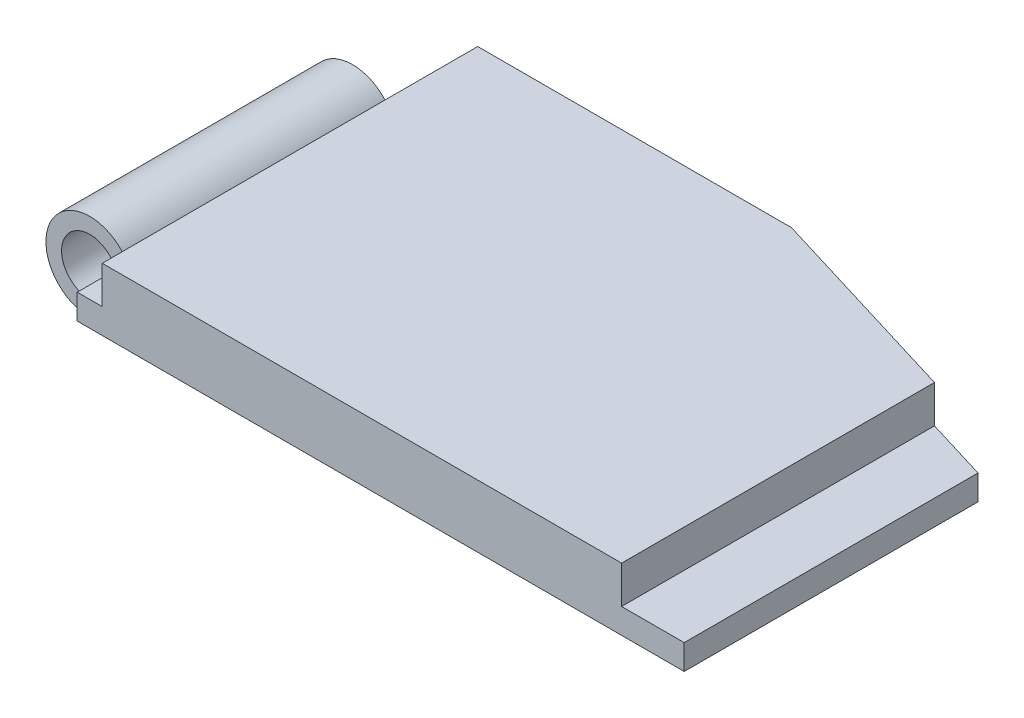
SolidWorks part; units mm, degrees
ref_plane "Front Plane" through (0, 0, 0) normal (0, 0, 1) x (1, 0, 0)
ref_plane "Top Plane" through (0, 0, 0) normal (0, 1, 0) x (1, 0, 0)
ref_plane "Right Plane" through (0, 0, 0) normal (1, 0, 0) x (0, 0, -1)
sketch "Sketch1" plane through (0, 0, 0) normal (0, 1, 0) x (1, 0, 0)
  line L1 (0, 0) -> (52, 0)
  line L2 (0, 0) -> (0, -30)
  line L3 (0, -30) -> (52, -30)
  line L4 (52, 0) -> (52, -30)
  dimension "D1" = 52
  dimension "D2" = 30
extrude "Boss-Extrude1" add sketch "Sketch1" along normal blind 2
sketch "Sketch3" plane through (0, 0, 0) normal (0, -1, 0) x (1, 0, 0)
  line L0 (0, 30) -> (52, 30) construction
  line L1 (23, 17.6) -> (29, 17.6)
  line L2 (23, 17.6) -> (23, 14.6)
  line L3 (23, 14.6) -> (29, 14.6)
  line L4 (29, 17.6) -> (29, 14.6)
  line L5 (52, 30) -> (52, 0) construction
  dimension "D1" = 12.4
  dimension "D2" = 3
  dimension "D3" = 6
  dimension "D4" = 29
extrude "Boss-Extrude3" add sketch "Sketch3" along normal blind 7
sketch "Sketch4" plane through (0, 0, 17.6) normal (0, 0, 1) x (1, 0, 0)
  line L0 (29, -7) -> (23, -7) construction
  circle A0 centre (26, -4) radius 1
  point P5 (26, -7)
  dimension "D1" = 2
  dimension "D2" = 3
extrude "Cut-Extrude1" cut sketch "Sketch4" against normal through all
ref_plane "Plane1" through (0, 0, 15) normal (0, 0, 1) x (1, 0, 0)
sketch "Sketch5" plane through (0, 0, 15) normal (0, 0, 1) x (1, 0, 0)
  line L0 (0, 2) -> (52, 2) construction
  circle A0 centre (0, -0.25) radius 2.25
  circle A1 centre (0, -0.25) radius 3.5
  dimension "D1" = 4.5
  dimension "D2" = 7
extrude "Boss-Extrude4" add sketch "Sketch5" along normal blind 10.5 and the other way blind 10.5 separate body
sketch "Sketch6" plane through (0, 0, 30) normal (0, 0, 1) x (1, 0, 0)
  circle A0 centre (0, -0.25) radius 2.25
  circle A1 centre (0, -0.25) radius 2.25 construction
extrude "Cut-Extrude2" cut sketch "Sketch6" against normal through all
sketch "Sketch7" plane through (0, 2, 0) normal (0, 1, 0) x (1, 0, 0)
  line L0 (0, 0) -> (0, -30) construction
  line L1 (-1.2698, -25.5) -> (3.5, -25.5)
  line L2 (-1.2698, -25.5) -> (-1.2698, -30.3543)
  line L3 (-1.2698, -30.3543) -> (3.5, -30.3543)
  line L4 (3.5, -25.5) -> (3.5, -30.3543)
  line L5 (0, -4.5) -> (3.5, -4.5)
  line L6 (0, -4.5) -> (0, 2.762)
  line L7 (0, 2.762) -> (3.5, 2.762)
  line L8 (3.5, -4.5) -> (3.5, 2.762)
  line L9 (-3.5, -25.5) -> (3.5, -25.5) construction
  line L10 (2.25, -4.5) -> (-2.25, -4.5) construction
  dimension "D1" = 3.5
extrude "Cut-Extrude3" cut sketch "Sketch7" against normal through all
sketch "Sketch8" plane through (0, 2, 0) normal (0, 1, 0) x (1, 0, 0)
  line L0 (52, 0) -> (3.5, 0) construction
  line L1 (47, 0) -> (5.5, 0)
  line L2 (47, 0) -> (47, -30)
  line L3 (47, -30) -> (5.5, -30)
  line L4 (5.5, 0) -> (5.5, -30)
  line L5 (3.5, -30) -> (52, -30) construction
  line L6 (52, -30) -> (52, 0) construction
  line L7 (3.5, -30) -> (3.5, -25.5) construction
  dimension "D1" = 5
  dimension "D2" = 2
extrude "Boss-Extrude5" add sketch "Sketch8" along normal blind 3
sketch "Sketch9" plane through (0, 0, 0) normal (0, -1, 0) x (1, 0, 0)
  line L0 (30.5839, 0) -> (52, 6.5236)
  line L1 (52, 0) -> (3.5, 0) construction
  line L2 (52, 30) -> (52, 0) construction
  line L3 (52, 6.5236) -> (52, -3.8456)
  line L4 (52, -3.8456) -> (30.5839, -3.8456)
  line L5 (30.5839, -3.8456) -> (30.5839, 0)
extrude "Cut-Extrude4" cut sketch "Sketch9" against normal through all
